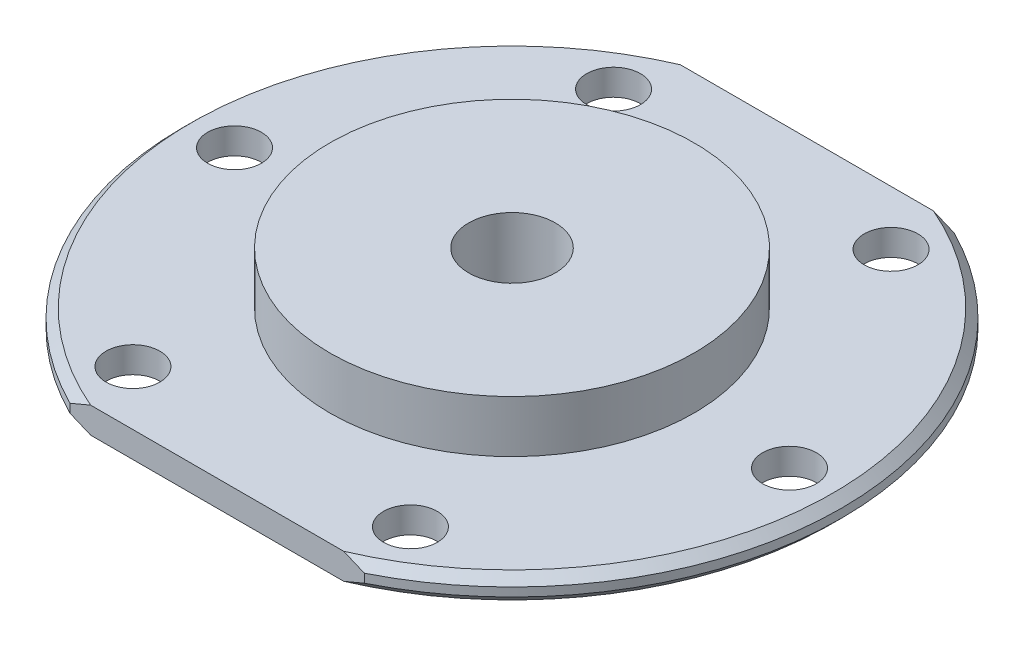
SolidWorks part; units mm, degrees
ref_plane "Front Plane" through (0, 0, 0) normal (0, 0, 1) x (1, 0, 0)
ref_plane "Top Plane" through (0, 0, 0) normal (0, 1, 0) x (1, 0, 0)
ref_plane "Right Plane" through (0, 0, 0) normal (1, 0, 0) x (0, 0, -1)
sketch "Sketch1" plane through (0, 0, 0) normal (0, 1, 0) x (1, 0, 0)
  line L0 (-8.4853, 17) -> (8.4853, 17)
  line L1 (-8.4853, -17) -> (8.4853, -17)
  arc A0 (8.4853, -17) -> (8.4853, 17) centre (0, 0) ccw
  circle A1 centre (0, 0) radius 16 construction
  arc A2 (-8.4853, 17) -> (-8.4853, -17) centre (0, 0) ccw
  circle A3 centre (-16, 0) radius 1.55
  circle A4 centre (-8, 13.8564) radius 1.55
  circle A5 centre (8, 13.8564) radius 1.55
  circle A6 centre (16, 0) radius 1.55
  circle A7 centre (8, -13.8564) radius 1.55
  circle A8 centre (-8, -13.8564) radius 1.55
  point P10 (0, 0)
  point P11 (0, 0)
  point P21 (0, 0)
  dimension "D1" = 38
  dimension "D2" = 32
  dimension "D5" = 3.1
  dimension "D3" = 17
  dimension "D4" = 17
  dimension "D6" = 6
extrude "Boss-Extrude1" add sketch "Sketch1" along normal blind 1.5
sketch "Sketch2" plane through (0, 1.5, 0) normal (0, 1, 0) x (1, 0, 0)
  circle A0 centre (0, 0) radius 10.5
  dimension "D1" = 21
extrude "Boss-Extrude2" add sketch "Sketch2" along normal blind 3
sketch "Sketch3" plane through (0, 0, 0) normal (0, -1, 0) x (1, 0, 0)
  circle A0 centre (0, 0) radius 5
  dimension "D1" = 10
extrude "Boss-Extrude3" add sketch "Sketch3" along normal blind 5
sketch "Sketch4" plane through (0, 4.5, 0) normal (0, 1, 0) x (1, 0, 0)
  circle A0 centre (0, 0) radius 2.5
  dimension "D1" = 5
extrude "Cut-Extrude1" cut sketch "Sketch4" against normal through all
chamfer "Chamfer1" distance 0.5 angle 45 6 edges at (0, -5, -5) (0, -5, 2.5) (19, 0, 0) (19, 1.5, 0) (-19, 0, 0) (-19, 1.5, 0)
